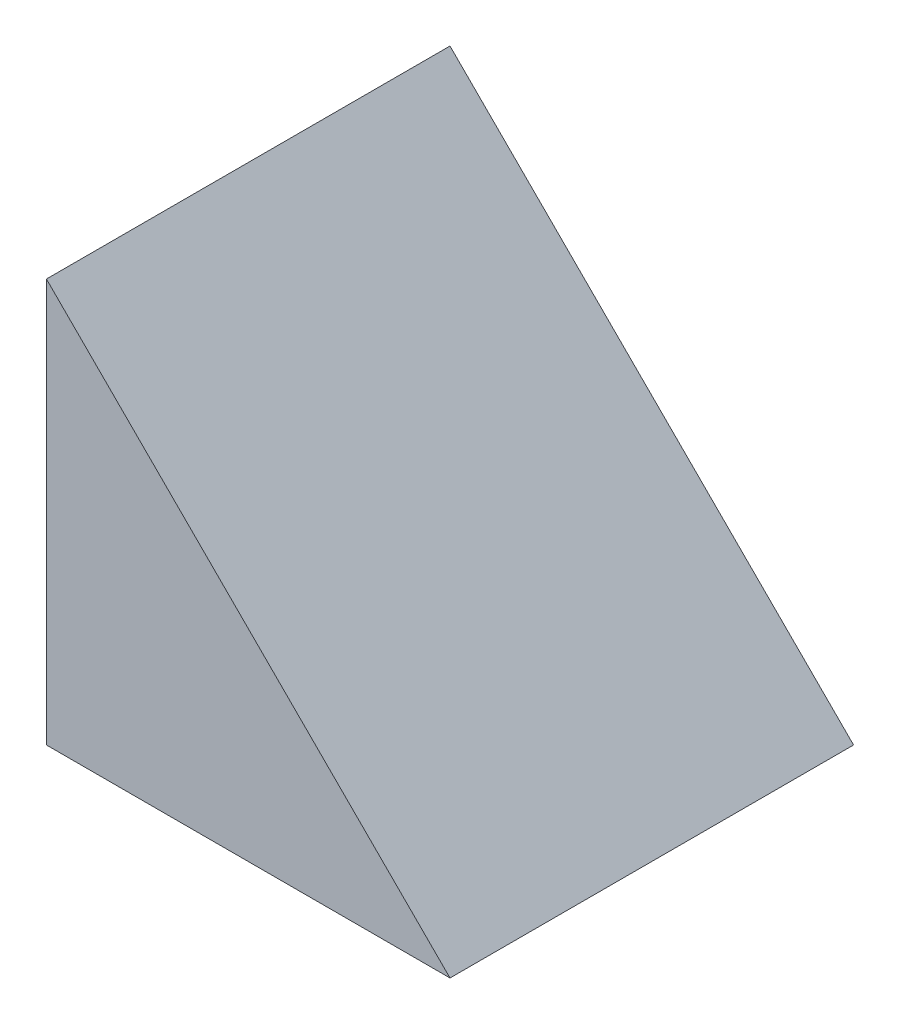
SolidWorks part; units mm, degrees
ref_plane "前基準面" through (0, 0, 0) normal (0, 0, 1) x (1, 0, 0)
ref_plane "上基準面" through (0, 0, 0) normal (0, 1, 0) x (1, 0, 0)
ref_plane "右基準面" through (0, 0, 0) normal (1, 0, 0) x (0, 0, -1)
sketch "草圖1" plane through (0, 0, 0) normal (0, 0, 1) x (1, 0, 0)
  line L0 (0, 0) -> (0, 20)
  line L1 (0, 20) -> (20, 0)
  line L2 (20, 0) -> (0, 0)
  dimension "D1" = 20
  dimension "D2" = 20
extrude "填料-伸長1" add sketch "草圖1" along normal blind 20
